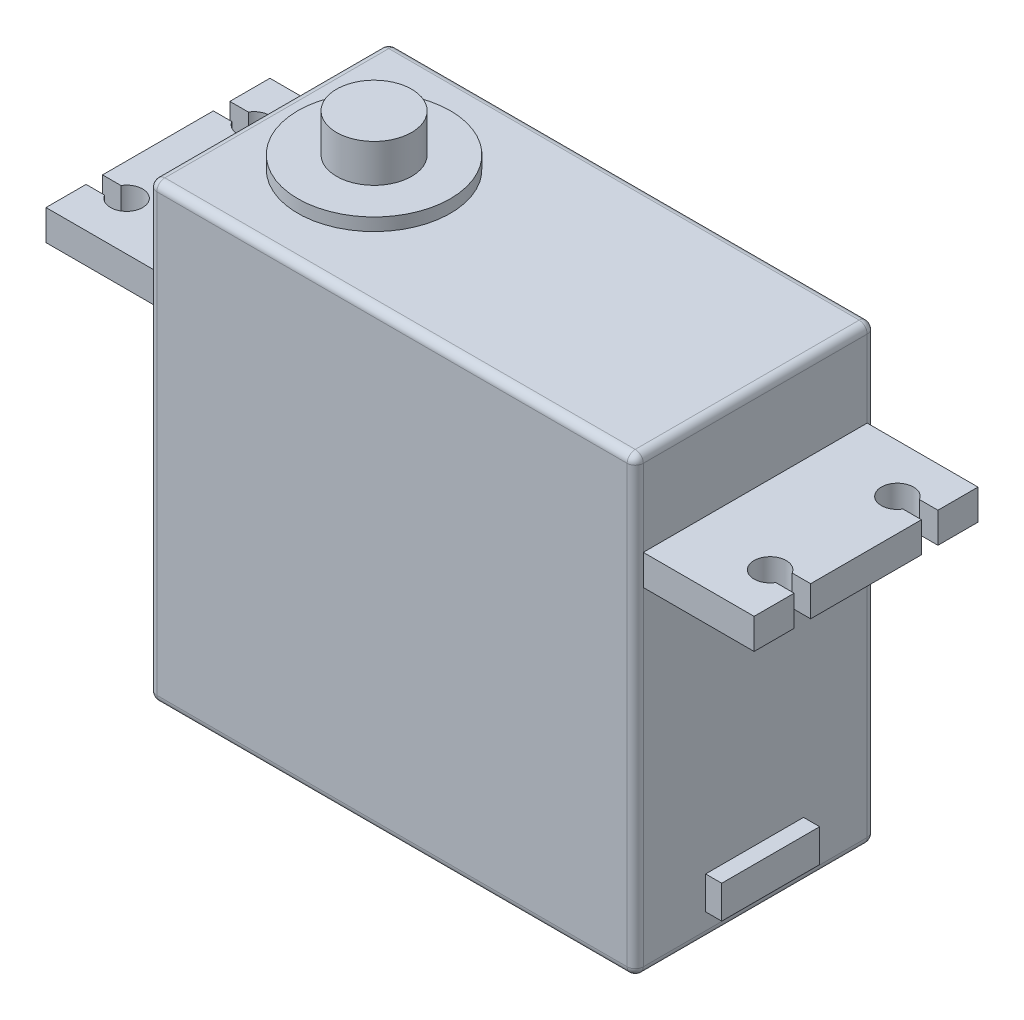
SolidWorks part; units mm, degrees
material "PPS"
ref_plane "Front Plane" through (0, 0, 0) normal (0, 0, 1) x (1, 0, 0)
ref_plane "Top Plane" through (0, 0, 0) normal (0, 1, 0) x (1, 0, 0)
ref_plane "Right Plane" through (0, 0, 0) normal (1, 0, 0) x (0, 0, -1)
sketch "Sketch1" plane through (0, 0, 0) normal (0, 0, 1) x (1, 0, 0)
  line L0 (0, 0) -> (38.37, 0)
  line L1 (38.37, 0) -> (38.37, 35.66)
  line L2 (38.37, 35.66) -> (0, 35.66)
  line L3 (0, 35.66) -> (0, 0)
extrude "Boss-Extrude1" add sketch "Sketch1" along normal blind 18.93
fillet "Fillet1" radius 0.635 12 edges at (19.185, 0, 18.93) (19.185, 35.66, 18.93) (38.37, 0, 9.465) (38.37, 17.83, 18.93) (38.37, 35.66, 9.465) (38.37, 17.83, 0) (19.185, 35.66, 0) (19.185, 0, 0) (0, 0, 9.465) (0, 17.83, 18.93) (0, 35.66, 9.465) (0, 17.83, 0)
sketch "Sketch2" plane through (0, 0, 18.93) normal (0, 0, 1) x (1, 0, 0)
  text T0 "<b>SPEKTRUM</b>\r\n<b>           A6380</b>" font "Constantia" height 3.5
sketch "Sketch3" plane through (0, 0, 0) normal (-1, 0, 0) x (0, 0, 1)
  line L0 (0.635, 28.945) -> (18.295, 28.945)
  line L5 (18.295, 0.635) -> (18.295, 35.025) construction
  line L6 (18.295, 28.945) -> (18.295, 26.545)
  line L7 (18.295, 26.545) -> (0.635, 26.545)
  line L8 (0.635, 35.025) -> (0.635, 0.635) construction
  line L9 (0.635, 26.545) -> (0.635, 28.945)
sketch "Sketch4" plane through (0, 35.66, 0) normal (0, 1, 0) x (1, 0, 0)
  line L3 (19.185, -0.635) -> (19.185, -18.295)
  line L4 (37.735, -0.635) -> (0.635, -0.635) construction
  line L5 (0.635, -18.295) -> (37.735, -18.295) construction
ref_plane "Plane1" through (19.185, 0, 0) normal (-1, 0, 0) x (0, 0, 1)
extrude "Boss-Extrude2" add sketch "Sketch3" along normal blind 8.74
sketch "Sketch5" plane through (0, 35.66, 0) normal (0, 1, 0) x (1, 0, 0)
  circle A0 centre (8.3079, -9.465) radius 6.015
extrude "Boss-Extrude3" add sketch "Sketch5" along normal blind 1
sketch "Sketch7" plane through (0, 36.66, 0) normal (0, 1, 0) x (1, 0, 0)
  circle A0 centre (8.3079, -9.465) radius 2.96
extrude "Boss-Extrude4" add sketch "Sketch7" along normal blind 3
sketch "Sketch8" plane through (38.37, 0, 0) normal (1, 0, 0) x (0, 0, -1)
  line L0 (-5.655, 4.5213) -> (-5.655, 1.9315)
  line L3 (-5.655, 4.5213) -> (-13.3785, 4.5213)
  line L4 (-13.3785, 4.5213) -> (-13.3785, 1.9315)
  line L5 (-13.3785, 1.9315) -> (-5.655, 1.9315)
extrude "Boss-Extrude5" add sketch "Sketch8" along normal blind 1.27
sketch "Sketch9" plane through (0, 28.945, 0) normal (0, 1, 0) x (1, 0, 0)
  line L5 (-8.74, -5.0949) -> (-7.2853, -5.0949)
  line L6 (-8.74, -18.295) -> (-8.74, -0.635) construction
  line L7 (-8.74, -13.8351) -> (-8.74, -15.1349)
  line L8 (-8.74, -13.8351) -> (-7.2853, -13.8351)
  line L9 (-8.74, -5.0949) -> (-8.74, -3.7951)
  line L10 (-8.74, -3.7951) -> (-7.2853, -3.7951)
  line L11 (-8.74, -15.1349) -> (-7.2853, -15.1349)
  arc A0 (-7.2853, -5.0949) -> (-7.2853, -3.7951) centre (-6.1941, -4.445) ccw
  arc A1 (-7.2853, -15.1349) -> (-7.2853, -13.8351) centre (-6.1941, -14.485) ccw
extrude "Cut-Extrude1" cut sketch "Sketch9" against normal up to next
mirror "Mirror3" about plane through (19.185, 0, 0) normal (-1, 0, 0) of "Boss-Extrude2", "Cut-Extrude1"
